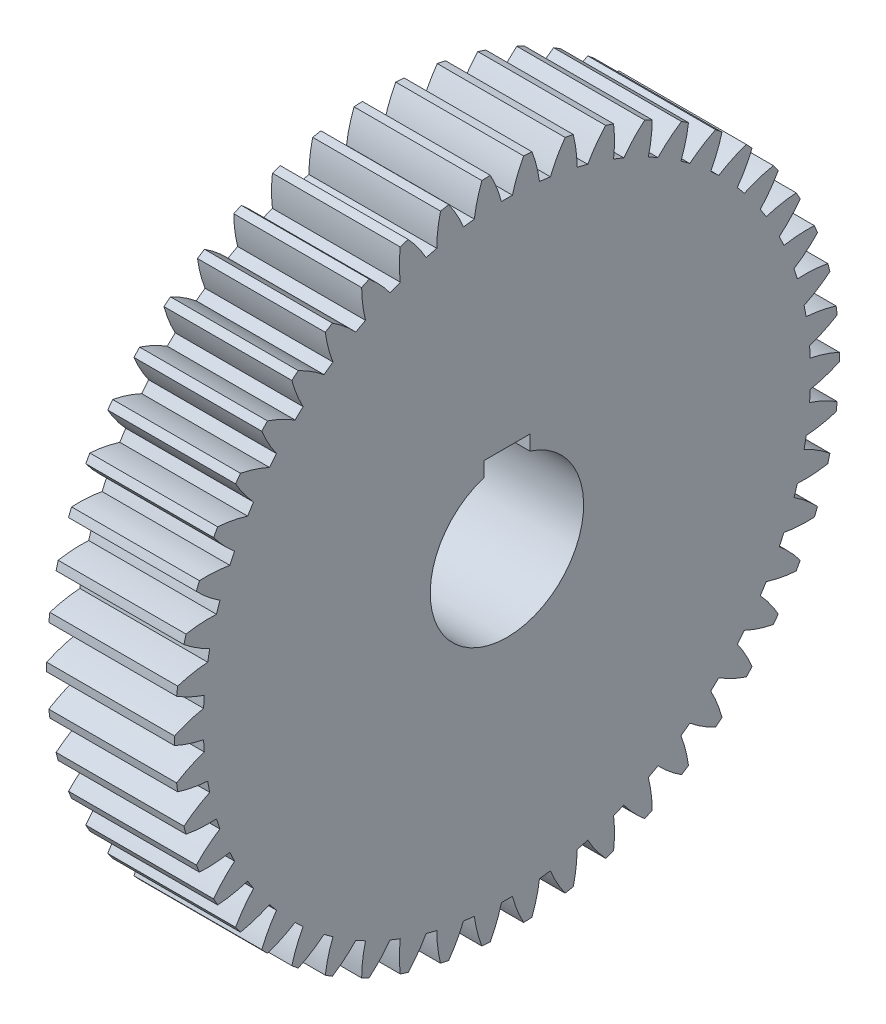
SolidWorks part; units mm, degrees
material "Gray Cast Iron"
ref_plane "Plane1" through (0, 0, 0) normal (0, 0, 1) x (1, 0, 0)
ref_plane "Plane2" through (0, 0, 0) normal (0, 1, 0) x (1, 0, 0)
ref_plane "Plane3" through (0, 0, 0) normal (1, 0, 0) x (0, 0, -1)
other "Configuration Table"
sketch "HoldingSke" plane through (0, 0, 0) normal (0, 1, 0) x (1, 0, 0)
  line L0 (0, 0) -> (0.1286, -0.1532)
  line L1 (-15, 0) -> (100, 0) construction
  line L2 (0, 0) -> (-2.1039, 2.3779)
  line L3 (0, 0) -> (-11.863, 4.5341)
  line L4 (0, 0) -> (5.5511, 6.6156)
  line L5 (0, 0) -> (-46.8476, -17.4728)
  line L6 (0, 0) -> (-41.4481, -27.9652)
  line L7 (-2.1039, 2.3779) -> (8.6586, 51.2059)
  line L8 (-76.2, 54.61) -> (-71.8, 54.61)
  line L9 (-71.009, 38.7566) -> (-53.1078, 45.2721)
  line L10 (-76.2, 71.12) -> (104.1128, 71.12)
  line L11 (0, 0) -> (-50, 0)
  line L12 (-76.2, 101.6) -> (-76.033, 101.6)
  line L13 (24.9733, 27.94) -> (52.9518, 28.4284)
  line L14 (24.9733, 27.94) -> (24.9743, 27.94)
  line L15 (24.9733, 27.94) -> (100.4006, 29.5858)
  line L16 (-63.627, -5) -> (-12.827, -5)
  circle A0 centre (0, 0) radius 30
  circle A1 centre (0, 0) radius 37.5
  circle A2 centre (0, 0) radius 37.5
  circle A3 centre (0, 0) radius 30
  dimension "MHD" = 75
  dimension "Hub_dia" = 75
  dimension "Bore" = 60
  dimension "MBD" = 60
  dimension "Num_teeth" = 50
  dimension "Pitch" = 0.2
  dimension "Overall_len" = 50
  dimension "Show_teeth" = 50
  dimension "Thickness" = 50
  dimension "OAL" = 50.0001
  dimension "T_dim" = 4.4
  dimension "Ap" = 20
  dimension "H" = 19.05
  dimension "Pitch_radius" = 180.3128
  dimension "Width" = 50
  dimension "Backlash" = 0.167
  dimension "Addendum_fac" = 1
  dimension "Dedendum_fac" = 1.25
  dimension "Clearance_fac" = 0.25
  dimension "Dedendum_add" = 0.001
  dimension "Module" = 5
sketch "BasProSke" plane through (0, 0, 0) normal (0, 1, 0) x (1, 0, 0)
  line L0 (-10, 0) -> (60, 0) construction
  line L1 (0, 0) -> (0, 130)
  line L2 (0, 0) -> (50, 0)
  line L3 (50, 0) -> (50, 130)
  line L4 (50, 130) -> (0, 130)
  dimension "Thickness" = 50
  dimension "Diameter" = 260
revolve "Base-Revolve" add sketch "BasProSke" angle 360 about L0
sketch "TooCutSke" plane through (0, 0, 0) normal (1, 0, 0) x (0, 0, -1)
  line L1 (0, 0) -> (0, 107) construction
  line L2 (0, 0) -> (-4.2186, 124.9288) construction
  line L3 (0, 0) -> (-15.691, 249.4012) construction
  line L4 (-4.2186, 124.9288) -> (-7.8455, 124.7006) construction
  arc A0 (2.1511, 118.7295) -> (-2.1511, 118.7295) centre (0, 0) ccw
  arc A1 (6.5515, 129.8602) -> (-6.5515, 129.8602) centre (0, 0) ccw
  circle A2 centre (0, 0) radius 125 construction
  circle A3 centre (0, 0) radius 117.4616 construction
  arc A4 (-2.1511, 118.7295) -> (-6.5515, 129.8602) centre (-50.5153, 106.0445) ccw
  arc A5 (6.5515, 129.8602) -> (2.1511, 118.7295) centre (50.5153, 106.0445) ccw
  dimension "Root_dia" = 237.498
  dimension "Overcut_dia" = 260.0508
  dimension "Pitch_dia" = 250
  dimension "Base_dia" = 234.9232
  dimension "Flank_rad" = 50
  dimension "Half_ang" = 3.6
  dimension "Half_CT" = 3.6341
extrude "ToothCut" cut sketch "TooCutSke" along normal through all
fillet "Breaks" [suppressed] radius 0.1
fillet "RootFillets" [suppressed] radius 1.251
pattern_circular "TeethCuts" count 50 every 7.2 about axis through (-10, 0, 0) along (1, 0, 0) of "ToothCut", "RootFillets", "Breaks"
sketch "HubNeaOneSke" plane through (0, 0, 0) normal (-1, 0, 0) x (0, 0, 1)
  circle A0 centre (0, 0) radius 37.5
  dimension "Diameter" = 75
extrude "HubNearOne" [suppressed] add sketch "HubNeaOneSke" along normal blind 38.0001
sketch "HubNeaBotSke" plane through (0, 0, 0) normal (-1, 0, 0) x (0, 0, 1)
  circle A0 centre (0, 0) radius 37.5
  dimension "Diameter" = 75
extrude "HubNearBoth" [suppressed] add sketch "HubNeaBotSke" along normal blind 19
ref_plane "FarPln" through (50, 0, 0) normal (1, 0, 0) x (0, 0, -1)
sketch "HubFarSke" plane through (50, 0, 0) normal (1, 0, 0) x (0, 0, -1)
  circle A0 centre (0, 0) radius 37.5
  dimension "Diameter" = 75
extrude "HubFar" [suppressed] add sketch "HubFarSke" along normal blind 19
sketch "BorSke" plane through (0, 0, 0) normal (1, 0, 0) x (0, 0, -1)
  circle A0 centre (0, 0) radius 30
  dimension "Diameter" = 60
extrude "Bore" cut sketch "BorSke" along normal mid plane 100.0001
sketch "KeySke" plane through (0, 0, 0) normal (1, 0, 0) x (0, 0, -1)
  line L0 (-9, 0) -> (-9, 34.4)
  line L1 (-9, 34.4) -> (9, 34.4)
  line L2 (9, 34.4) -> (9, 0)
  line L3 (0, 0) -> (0, 34) construction
  line L4 (-9, 0) -> (9, 0)
  dimension "Offset" = 34.4
  dimension "Width" = 18
extrude "Keyway" cut sketch "KeySke" along normal mid plane 100.0001
pattern_circular "Keyway2" [suppressed] count 2 every 90 about axis through (-10, 0, 0) along (1, 0, 0)
equation "' \"Module@HoldingSke\" = 6.35"
equation "' \"Num_teeth@HoldingSke\" = 12"
equation "' \"Ap@HoldingSke\" =  20"
equation "' \"Ap@HoldingSke\" = 20"
equation "' \"Width@HoldingSke\" = 0.5 * 25.4"
equation "' \"Hub_dia@HoldingSke\"= 1 * 25.4"
equation "' \"Hub_dia@HoldingSke\" = 1 * 25.4"
equation "' \"Overall_len@HoldingSke\" = 1.0 * 25.4"
equation "' \"Bore@HoldingSke\" = 0.75 * 25.4"
equation "' \"T_dim@HoldingSke\" = 0.1 * 25.4"
equation "' \"Width@KeySke\" = 0.25 * 25.4"
equation "' \"Show_teeth@HoldingSke\" = 13"
equation "' \"Backlash@HoldingSke\" = 0.009 * 25.4"
equation "' \"Addendum_fac@HoldingSke\" = 1.0"
equation "' \"Dedendum_fac@HoldingSke\" = 1.25"
equation "' \"Dedendum_add@HoldingSke\" = 0.00005 * 25.4"
equation "' \"Clearance_fac@HoldingSke\" = 0.25"
equation "\"Pitch@HoldingSke\" = 1 / \"Module@HoldingSke\""
equation "\"Overcut_dia@TooCutSke\" = (\"Num_teeth@HoldingSke\" + 2 * \"Addendum_fac@HoldingSke\") / \"Pitch@HoldingSke\" + 0.002 * 25.4"
equation "\"Pitch_dia@TooCutSke\" = \"Num_teeth@HoldingSke\" / \"Pitch@HoldingSke\""
equation "\"Base_dia@TooCutSke\" = \"Num_teeth@HoldingSke\" / \"Pitch@HoldingSke\" * cos((\"Ap@HoldingSke\"  * 3.14159265 / 180))"
equation "\"Root_dia@TooCutSke\" = (\"Num_teeth@HoldingSke\" + 2) / \"Pitch@HoldingSke\" - 2 * (\"Addendum_fac@HoldingSke\" + \"Dedendum_fac@HoldingSke\") / \"Pitch@HoldingSke\" - \"Dedendum_add@HoldingSke\" * 2"
equation "\"Half_ang@TooCutSke\" = 180 / \"Num_teeth@HoldingSke\""
equation "\"Half_CT@TooCutSke\" = \"Num_teeth@HoldingSke\" / \"Pitch@HoldingSke\" * sin((3.14159265 / 2 / \"Num_teeth@HoldingSke\")) / 2 - 7 * \"Backlash@HoldingSke\" / 4"
equation "\"Flank_rad@TooCutSke\" = \"Num_teeth@HoldingSke\" / \"Pitch@HoldingSke\" / 5"
equation "\"Radius@RootFillets\" = \"Clearance_fac@HoldingSke\" / \"Pitch@HoldingSke\" + \"Dedendum_add@HoldingSke\""
equation "\"Break_rad@Breaks\" = 0.02 / \"Pitch@HoldingSke\""
equation "\"Thickness@HoldingSke\" = \"Width@HoldingSke\""
equation "\"OAL@HoldingSke\" = \"Thickness@HoldingSke\""
equation "\"MHD@HoldingSke\" = (\"Num_teeth@HoldingSke\" + 2) / \"Pitch@HoldingSke\" - 2 * (\"Addendum_fac@HoldingSke\" + \"Dedendum_fac@HoldingSke\")  / \"Pitch@HoldingSke\" - \"Dedendum_add@HoldingSke\" * 2"
equation "\"MBD@HoldingSke\" = (\"Num_teeth@HoldingSke\" + 2) / \"Pitch@HoldingSke\" - 2 * (\"Addendum_fac@HoldingSke\" + \"Dedendum_fac@HoldingSke\")  / \"Pitch@HoldingSke\" - \"Dedendum_add@HoldingSke\" * 2 - 0.002 * 25.4"
equation "\"MHD@HoldingSke\" = ((sgn( \"MHD@HoldingSke\" - \"Hub_dia@HoldingSke\" )-1)*( \"MHD@HoldingSke\" - \"Hub_dia@HoldingSke\" ))/-2+ \"Hub_dia@HoldingSke\""
equation "\"MBD@HoldingSke\" = ((sgn( \"MBD@HoldingSke\" - \"Bore@HoldingSke\" )-1)*( \"MBD@HoldingSke\" - \"Bore@HoldingSke\" ))/-2+ \"Bore@HoldingSke\""
equation "\"OAL@HoldingSke\" = ((sgn( \"OAL@HoldingSke\" - \"Overall_len@HoldingSke\" )+1)*( \"OAL@HoldingSke\" - \"Overall_len@HoldingSke\" ))/2 + \"Overall_len@HoldingSke\" + 0.000002 * 25.4"
equation "\"Num_teeth@TeethCuts\" = int( \"Show_teeth@HoldingSke\" ) + 1"
equation "\"Num_teeth@TeethCuts\" = ((sgn( \"Num_teeth@TeethCuts\" - \"Num_teeth@HoldingSke\" )-1)*( \"Num_teeth@TeethCuts\" - \"Num_teeth@HoldingSke\" ))/-2+ \"Num_teeth@HoldingSke\""
equation "\"Num_teeth@TeethCuts\" = ((sgn( \"Num_teeth@TeethCuts\" - 2.0)+1)*( \"Num_teeth@TeethCuts\" - 2.0))/2 +2.0"
equation "\"Angle@TeethCuts\" = 360.0 / \"Num_teeth@HoldingSke\""
equation "\"Diameter@BasProSke\" = (\"Num_teeth@HoldingSke\" + 2 * \"Addendum_fac@HoldingSke\") / \"Pitch@HoldingSke\""
equation "\"Thickness@BasProSke\"  = \"Thickness@HoldingSke\""
equation "' \"Fillet_rad@BasProSke\" =  \"Thickness@HoldingSke\" * 0.05"
equation "' \"Fillet_rad@BasProSke\" = \"Thickness@HoldingSke\" * 0.05"
equation "\"MHD@HoldingSke\" = ((sgn( \"MHD@HoldingSke\" - \"Root_dia@TooCutSke\" )-1)*( \"MHD@HoldingSke\" - \"Root_dia@TooCutSke\" ))/-2+ \"Root_dia@TooCutSke\""
equation "\"Diameter@HubNeaOneSke\" = \"MHD@HoldingSke\""
equation "\"Length@HubNearOne\" = \"OAL@HoldingSke\" - \"Thickness@BasProSke\""
equation "\"Diameter@HubNeaBotSke\" = \"MHD@HoldingSke\""
equation "\"Length@HubNearBoth\" = ( \"OAL@HoldingSke\" - \"Thickness@BasProSke\" ) / 2.0"
equation "\"Thickness@FarPln\" = \"Thickness@BasProSke\""
equation "\"Diameter@HubFarSke\" = \"MHD@HoldingSke\""
equation "\"Length@HubFar\" = ( \"OAL@HoldingSke\" - \"Thickness@BasProSke\" ) / 2.0"
equation "\"Diameter@BorSke\" = \"MBD@HoldingSke\""
equation "\"D1@Bore\" = \"OAL@HoldingSke\" * 2.0"
equation "\"D1@Keyway\" = \"OAL@HoldingSke\" * 2.0"
equation "\"Offset@KeySke\" = \"T_dim@HoldingSke\" + \"MBD@HoldingSke\" / 2.0"
